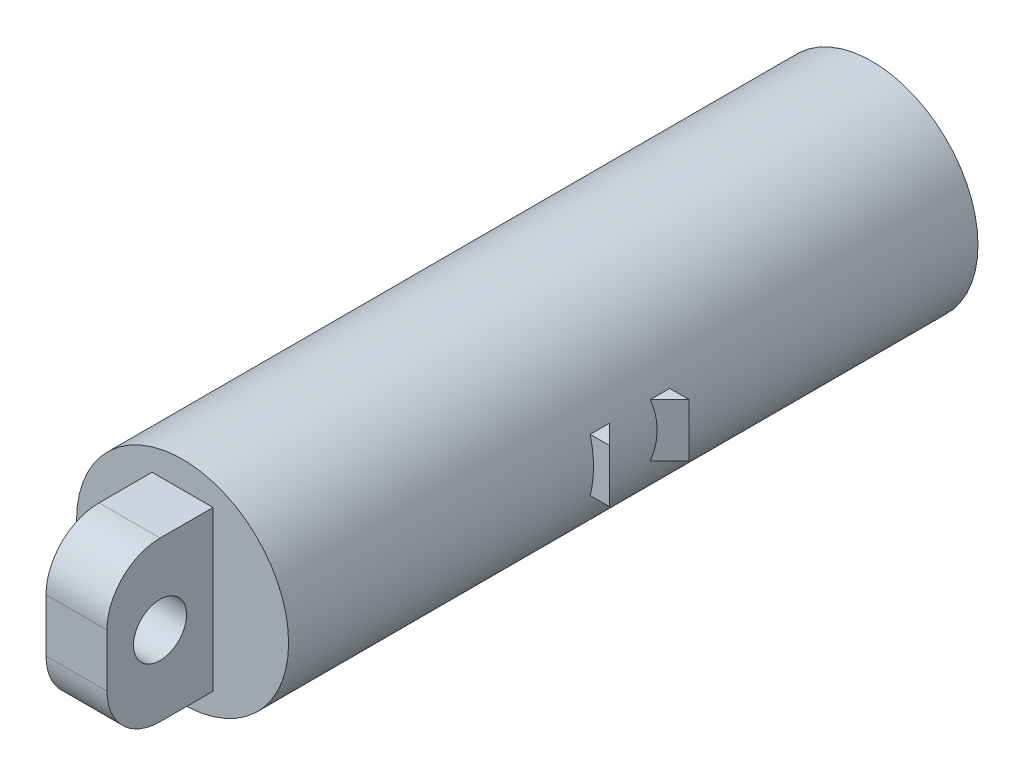
SolidWorks part; units mm, degrees
ref_plane "Front Plane" through (0, 0, 0) normal (0, 0, 1) x (1, 0, 0)
ref_plane "Top Plane" through (0, 0, 0) normal (0, 1, 0) x (1, 0, 0)
ref_plane "Right Plane" through (0, 0, 0) normal (1, 0, 0) x (0, 0, -1)
sketch "Sketch1" plane through (0, 0, 0) normal (0, 0, 1) x (1, 0, 0)
  circle A0 centre (0, 0) radius 20
  dimension "D1" = 40
extrude "Boss-Extrude1" add sketch "Sketch1" along normal blind 130
sketch "Sketch2" plane through (0, 0, 0) normal (0, 1, 0) x (1, 0, 0)
  line L0 (0, 0) -> (0, -130) construction
  line L1 (-20, -130) -> (20, -130) construction
  line L2 (0, -65) -> (31, -65) construction
  line L3 (23, -72.5) -> (15.5, -65)
  line L4 (23, -72.5) -> (8, -72.5)
  line L6 (23, -57.5) -> (8, -57.5)
  line L7 (8, -72.5) -> (8, -57.5)
  line L8 (23, -72.5) -> (8, -57.5) construction
  line L9 (23, -57.5) -> (8, -72.5) construction
  line L10 (15.5, -65) -> (23, -57.5)
  point P7 (15.5, -65)
  dimension "D1" = 15
  dimension "D2" = 15
  dimension "D3" = 8
extrude "Boss-Extrude2" add sketch "Sketch2" along normal mid plane 10
sketch "Sketch3" plane through (0, 0, 0) normal (0, 0, -1) x (-1, 0, 0)
  circle A0 centre (0, 0) radius 5
  dimension "D1" = 10
extrude "Boss-Extrude3" add sketch "Sketch3" along normal blind 10
sketch "Sketch4" plane through (0, 0, 130) normal (0, 0, 1) x (1, 0, 0)
  line L1 (5.75, 15) -> (-5.75, 15)
  line L2 (5.75, 15) -> (5.75, -15)
  line L3 (5.75, -15) -> (-5.75, -15)
  line L4 (-5.75, 15) -> (-5.75, -15)
  line L5 (5.75, 15) -> (-5.75, -15) construction
  line L6 (5.75, -15) -> (-5.75, 15) construction
  point P0 (0, 0)
  dimension "D1" = 30
  dimension "D2" = 11.5
extrude "Boss-Extrude4" add sketch "Sketch4" along normal blind 20
fillet "Fillet1" radius 10 2 edges at (0, 15, 150) (0, -15, 150)
sketch "Sketch5" plane through (5.75, 0, 0) normal (1, 0, 0) x (0, 0, -1)
  line L0 (-130, 0) -> (-150, 0) construction
  line L1 (-130, -15) -> (-130, 15) construction
  line L2 (-150, -5) -> (-150, 5) construction
  circle A0 centre (-140, 0) radius 5
  dimension "D1" = 10
extrude "Cut-Extrude1" cut sketch "Sketch5" against normal through all both and the other way through all
